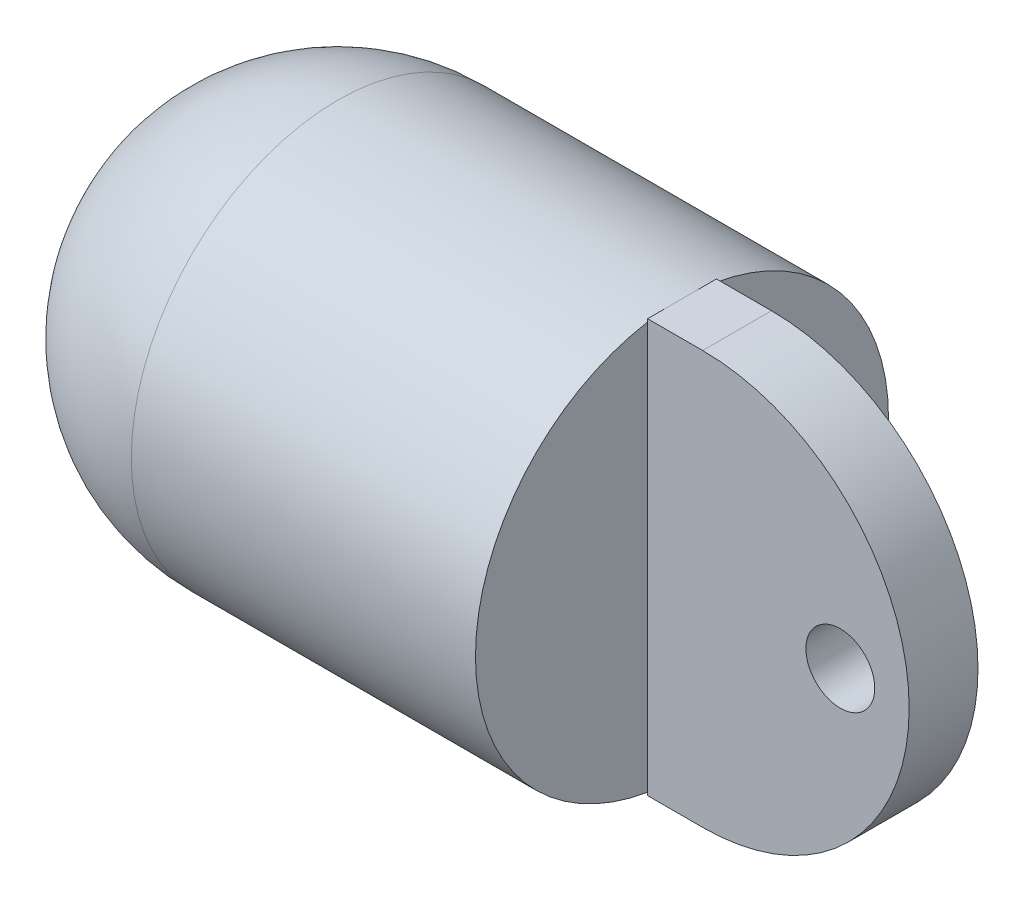
SolidWorks part; units mm, degrees
ref_plane "Front Plane" through (0, 0, 0) normal (0, 0, 1) x (1, 0, 0)
ref_plane "Top Plane" through (0, 0, 0) normal (0, 1, 0) x (1, 0, 0)
ref_plane "Right Plane" through (0, 0, 0) normal (1, 0, 0) x (0, 0, -1)
sketch "Sketch2" plane through (0, 0, 0) normal (1, 0, 0) x (0, 0, -1)
  circle A0 centre (0, 0) radius 15
  dimension "D1" = 30
extrude "Boss-Extrude1" add sketch "Sketch2" against normal blind 25
sketch "Sketch7" plane through (0, 0, 0) normal (1, 0, 0) x (0, 0, -1)
  line L0 (-2.5, 15) -> (-2.5, -15)
  line L1 (-2.5, 15) -> (2.5, 15)
  line L2 (-2.5, -15) -> (2.5, -15)
  line L3 (2.5, 15) -> (2.5, -15)
  line L4 (-2.5, 15) -> (2.5, -15) construction
  line L5 (-2.5, -15) -> (2.5, 15) construction
  point P1 (0, 0)
  dimension "D1" = 5
extrude "Boss-Extrude2" add sketch "Sketch7" along normal blind 4
sketch "Sketch8" plane through (0, 0, 2.5) normal (0, 0, 1) x (1, 0, 0)
  line L0 (4, 15) -> (4, -15) construction
  line L1 (4, 15) -> (4, -15)
  arc A0 (4, -15) -> (4, 15) centre (4, 0) ccw
extrude "Boss-Extrude3" add sketch "Sketch8" against normal blind 5
sketch "Sketch9" plane through (0, 0, 2.5) normal (0, 0, 1) x (1, 0, 0)
  circle A0 centre (14, 0) radius 2.5
  arc A1 (4, -15) -> (4, 15) centre (4, 0) ccw construction
  point P5 (19, 0)
  dimension "D1" = 5
  dimension "D2" = 5
extrude "Cut-Extrude3" cut sketch "Sketch9" against normal through all and the other way through all
sketch "Sketch10" plane through (-25, 0, 0) normal (-1, 0, 0) x (0, 0, 1)
  line L0 (0, 0) -> (0, 15)
  line L1 (0, 15) -> (0, -15)
  arc A0 (0, -15) -> (0, 15) centre (0, 0) ccw
revolve "Revolve1" add sketch "Sketch10" angle 360 about L1
